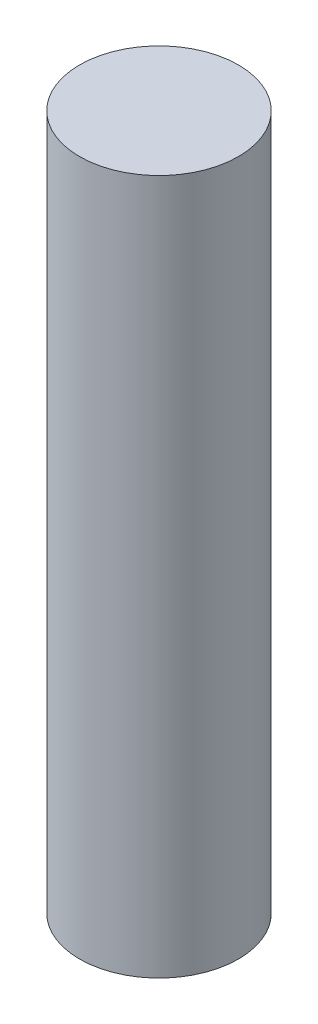
SolidWorks part; units mm, degrees
ref_plane "Front Plane" through (0, 0, 0) normal (0, 0, 1) x (1, 0, 0)
ref_plane "Top Plane" through (0, 0, 0) normal (0, 1, 0) x (1, 0, 0)
ref_plane "Right Plane" through (0, 0, 0) normal (1, 0, 0) x (0, 0, -1)
sketch "Sketch1" plane through (0, 0, 0) normal (0, 1, 0) x (1, 0, 0)
  circle A0 centre (0, 0) radius 4
  dimension "D1" = 8
extrude "Boss-Extrude1" add sketch "Sketch1" along normal mid plane 35
